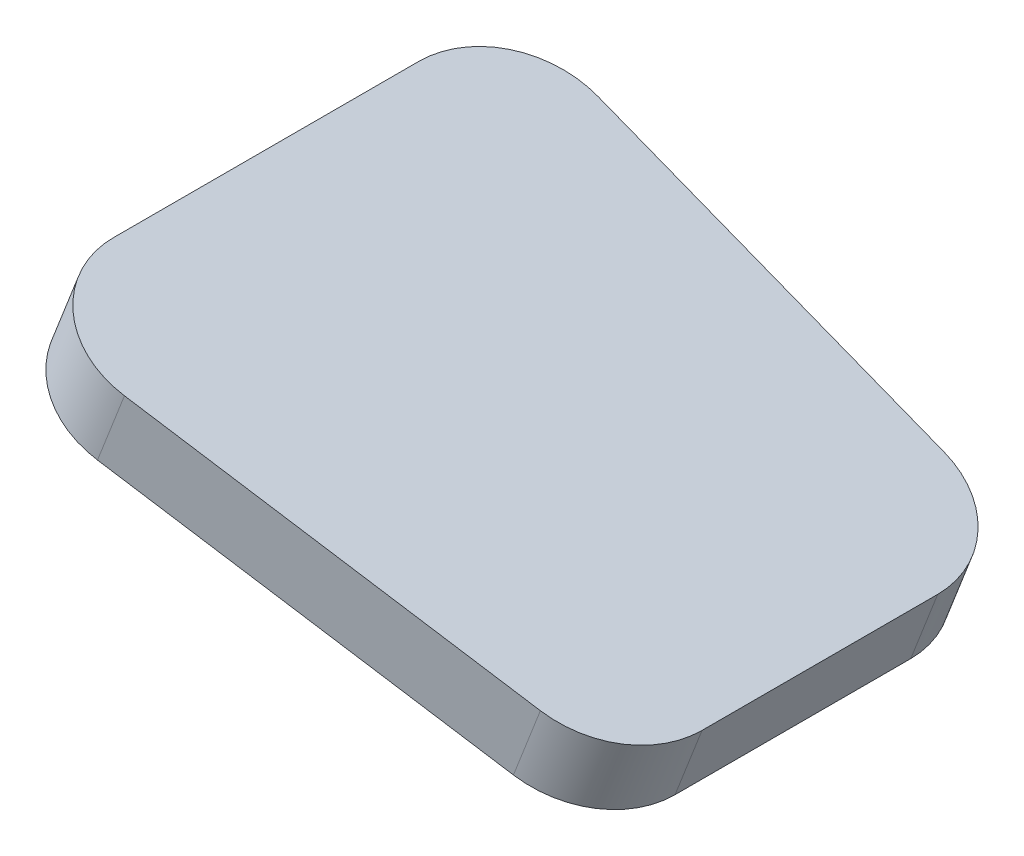
SolidWorks part; units mm, degrees
ref_plane "Front Plane" through (0, 0, 0) normal (0, 0, 1) x (1, 0, 0)
ref_plane "Top Plane" through (0, 0, 0) normal (0, 1, 0) x (1, 0, 0)
ref_plane "Right Plane" through (0, 0, 0) normal (1, 0, 0) x (0, 0, -1)
sketch "Sketch1" plane through (-4.899, -12.573, 0) normal (0.3631, 0.9318, 0) x (0.9318, -0.3631, 0)
  line L4 (-64.2849, -52.4622) -> (-51.5849, -50.0669)
  line L5 (-48.9983, -46.9469) -> (-48.9983, -38.8845)
  line L6 (-52.1733, -35.7095) -> (-64.8733, -35.7095)
  line L7 (-68.0483, -38.8845) -> (-68.0483, -49.3422)
  line L8 (-64.2849, -52.4622) -> (-51.5849, -50.0669)
  line L9 (-48.9983, -46.9469) -> (-48.9983, -38.8845)
  line L10 (-52.1733, -35.7095) -> (-64.8733, -35.7095)
  line L11 (-68.0483, -38.8845) -> (-68.0483, -49.3422)
  arc A4 (-68.0483, -49.3422) -> (-64.2849, -52.4622) centre (-64.8733, -49.3422) ccw
  arc A5 (-51.5849, -50.0669) -> (-48.9983, -46.9469) centre (-52.1733, -46.9469) ccw
  arc A6 (-48.9983, -38.8845) -> (-52.1733, -35.7095) centre (-52.1733, -38.8845) ccw
  arc A7 (-64.8733, -35.7095) -> (-68.0483, -38.8845) centre (-64.8733, -38.8845) ccw
  arc A8 (-68.0483, -49.3422) -> (-64.2849, -52.4622) centre (-64.8733, -49.3422) ccw
  arc A9 (-51.5849, -50.0669) -> (-48.9983, -46.9469) centre (-52.1733, -46.9469) ccw
  arc A10 (-48.9983, -38.8845) -> (-52.1733, -35.7095) centre (-52.1733, -38.8845) ccw
  arc A11 (-64.8733, -35.7095) -> (-68.0483, -38.8845) centre (-64.8733, -38.8845) ccw
  dimension "D1" = 0
extrude "Boss-Extrude1" add sketch "Sketch1" along normal blind 2.54
